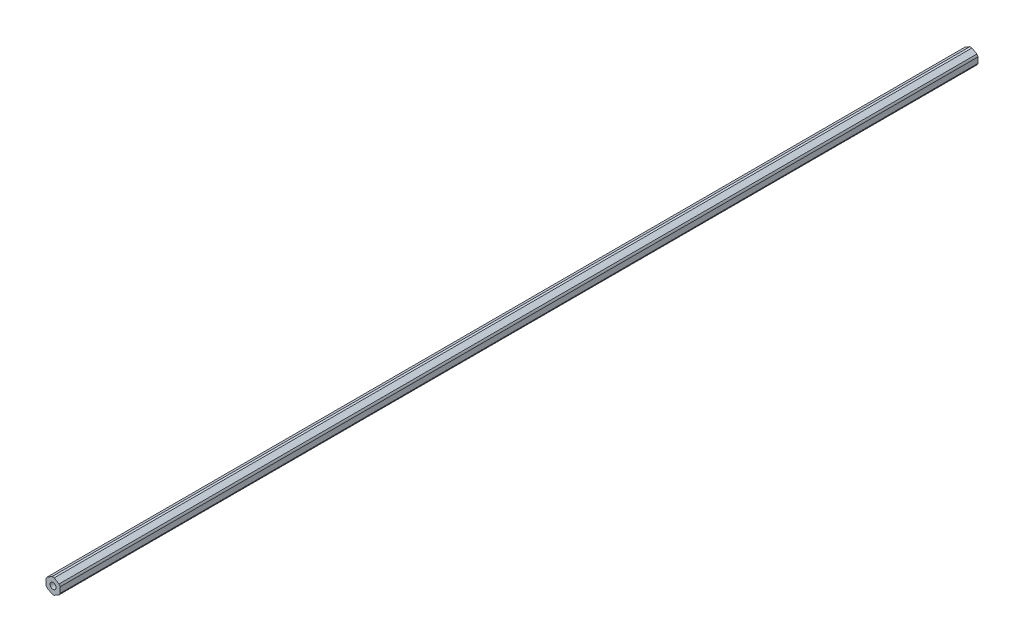
SolidWorks part; units mm, degrees
material "7075-T6 (SN)"
ref_plane "Front Plane" through (0, 0, 0) normal (0, 0, 1) x (1, 0, 0)
ref_plane "Top Plane" through (0, 0, 0) normal (0, 1, 0) x (1, 0, 0)
ref_plane "Right Plane" through (0, 0, 0) normal (1, 0, 0) x (0, 0, -1)
sketch "Sketch2" plane through (0, 0, 0) normal (0, 0, 1) x (1, 0, 0)
  line L1 (0, 5.4993) -> (-4.7625, 2.7496)
  line L2 (-4.7625, 2.7496) -> (-4.7625, -2.7496)
  line L3 (-4.7625, -2.7496) -> (0, -5.4993)
  line L4 (0, -5.4993) -> (4.7625, -2.7496)
  line L5 (4.7625, -2.7496) -> (4.7625, 2.7496)
  line L6 (4.7625, 2.7496) -> (0, 5.4993)
  circle A0 centre (0, 0) radius 4.7625 construction
  circle A2 centre (0, 0) radius 2.0193
  circle A3 centre (0, 0) radius 5.125
  dimension "D1" = 9.525
  dimension "D2" = 10.25
  dimension "D3" = 4.0386
extrude "Boss-Extrude1" add sketch "Sketch2" along normal mid plane 615.95 contours L5 A3 L6 L1 L2 L3 L4 A2
hole_wizard "#10-32 Tapped Hole2" positions "3DSketch1" profile "Sketch6" tap size "#10-32" standard "ANSI Inch"
sketch3d "3DSketch1"
  circle A0 centre (0, 0, 307.975) radius 2.0193 construction
  circle A1 centre (0, 0, -307.975) radius 2.0193 construction
  point P0 (0, 0, -307.975)
  point P2 (0, 0, 307.975)
  point P7 (0, 0, 309.9943)
  point P10 (0, 0, -305.9557)
sketch "Sketch6" plane through (0, 0, -307.975) normal (1, 0, 0) x (0, 1, 0)
  line L0 (0, 0) -> (0, 17.5608)
  line L1 (0, 17.5608) -> (2.0193, 16.3474)
  line L2 (2.0193, 16.3474) -> (2.0193, 0)
  line L5 (2.0193, 0) -> (0, 0)
  line L10 (0, 17.5608) -> (-2.0193, 16.3474) construction
  line L11 (0, -6.35) -> (0, 107.95) construction
  dimension "Tap Drill Dia." = 4.0386
  dimension "Tap Drill Depth" = 16.3474
  dimension "Drill Angle" = 118
cosmetic thread "Hole Thread2" parameters "D1"=13.97, "D2"=4.826
cosmetic thread "Hole Thread3" parameters "D1"=13.97, "D2"=4.826
equation "\"D2@Sketch2\"=10.25mm"
